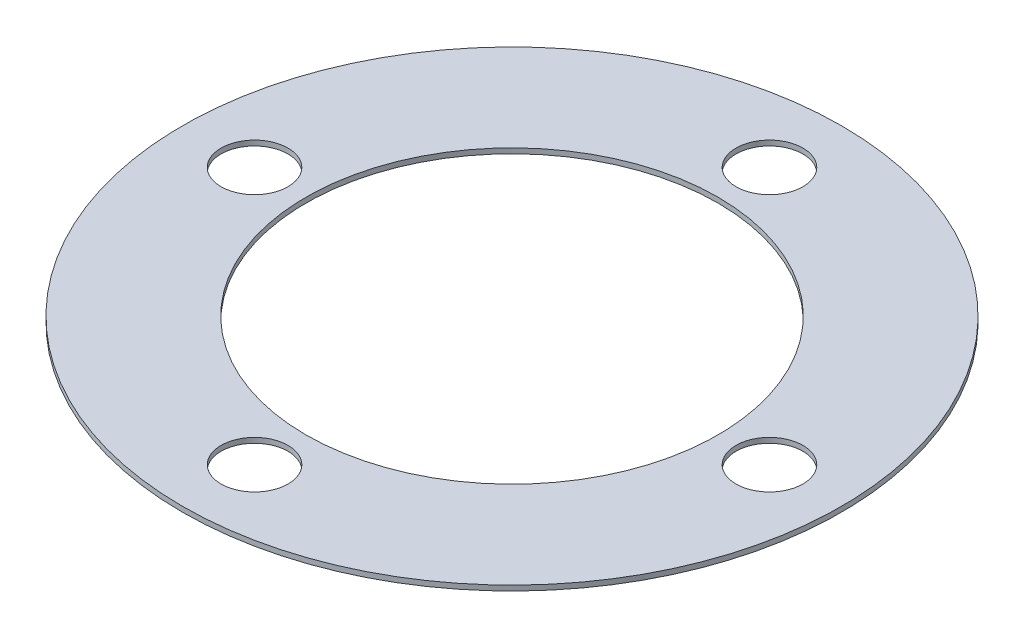
SolidWorks part; units mm, degrees
ref_plane "Front Plane" through (0, 0, 0) normal (0, 0, 1) x (1, 0, 0)
ref_plane "Top Plane" through (0, 0, 0) normal (0, 1, 0) x (1, 0, 0)
ref_plane "Right Plane" through (0, 0, 0) normal (1, 0, 0) x (0, 0, -1)
sketch "Sketch2" plane through (0, 0, 0) normal (0, 1, 0) x (1, 0, 0)
  circle A0 centre (0, 0) radius 32
  circle A1 centre (0, 0) radius 25 construction
  circle A2 centre (0, 0) radius 20
  circle A3 centre (0, 25) radius 3.25
  circle A4 centre (25, 0) radius 3.25
  circle A5 centre (0, -25) radius 3.25
  circle A6 centre (-25, 0) radius 3.25
  point P16 (0, 0)
  dimension "D1" = 64
  dimension "D2" = 50
  dimension "D3" = 40
  dimension "D4" = 6.5
  dimension "D5" = 4
extrude "Boss-Extrude1" add sketch "Sketch2" along normal blind 0.5
